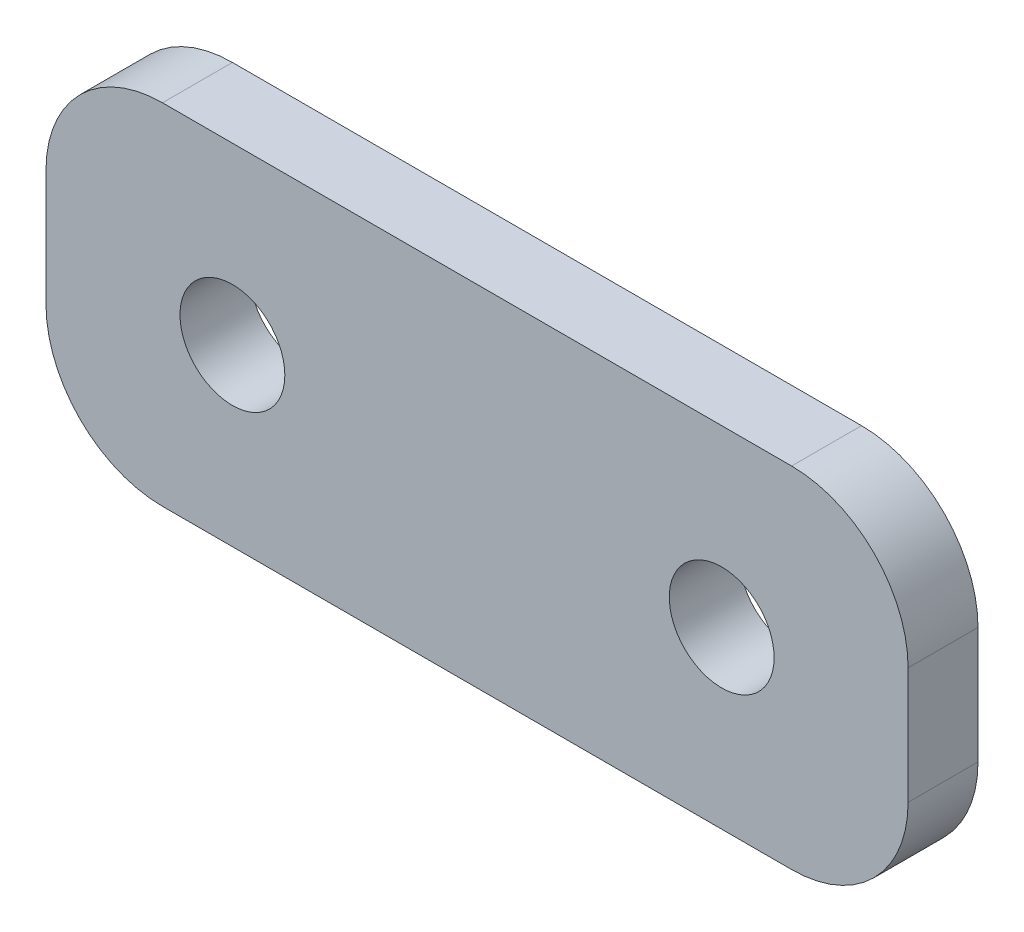
SolidWorks part; units mm, degrees
ref_plane "Front Plane" through (0, 0, 0) normal (0, 0, 1) x (1, 0, 0)
ref_plane "Top Plane" through (0, 0, 0) normal (0, 1, 0) x (1, 0, 0)
ref_plane "Right Plane" through (0, 0, 0) normal (1, 0, 0) x (0, 0, -1)
sketch "Sketch1" plane through (0, 0, 0) normal (0, 0, 1) x (1, 0, 0)
  line L13 (-13.5, -7.5) -> (13.5, -7.5)
  line L14 (-18.5, -2.5) -> (-18.5, 2.5)
  line L15 (-13.5, 7.5) -> (13.5, 7.5)
  line L16 (18.5, -2.5) -> (18.5, 2.5)
  circle A10 centre (-10.5, 0) radius 2.25
  circle A11 centre (10.5, 0) radius 2.25
  arc A16 (13.5, 7.5) -> (18.5, 2.5) centre (13.5, 2.5) cw
  arc A17 (13.5, -7.5) -> (18.5, -2.5) centre (13.5, -2.5) ccw
  arc A18 (-13.5, -7.5) -> (-18.5, -2.5) centre (-13.5, -2.5) cw
  arc A19 (-18.5, 2.5) -> (-13.5, 7.5) centre (-13.5, 2.5) cw
  point P0 (0, 0)
  point P2 (0, 0)
  point P6 (0, 0)
  point P8 (0, 0)
  dimension "D4" = 4.5
  dimension "D5" = 4.5
  dimension "D7" = 5
  dimension "D6" = 15
extrude "Boss-Extrude1" add sketch "Sketch1" along normal blind 3
